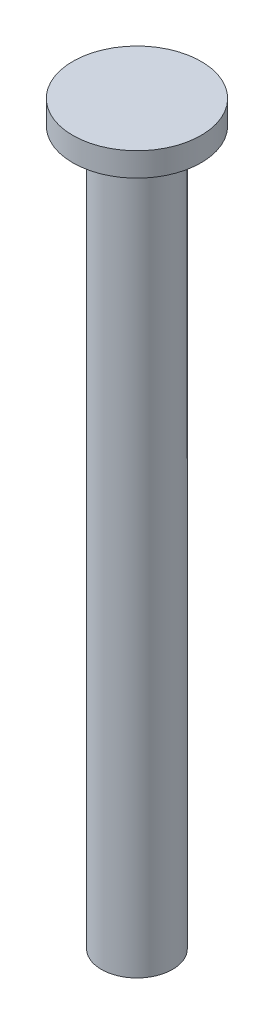
SolidWorks part; units mm, degrees
material "AISI 304"
ref_plane "Ön Düzlem" through (0, 0, 0) normal (0, 0, 1) x (1, 0, 0)
ref_plane "Üst Düzlem" through (0, 0, 0) normal (0, 1, 0) x (1, 0, 0)
ref_plane "Sağ Düzlem" through (0, 0, 0) normal (1, 0, 0) x (0, 0, -1)
sketch "Çizim2" plane through (0, 0, 0) normal (0, 1, 0) x (1, 0, 0)
  circle A0 centre (0, 0) radius 2.7
extrude "Yükseklik-Ekstrüzyon1" add sketch "Çizim2" along normal blind 1
sketch "Çizim3" plane through (0, 0, 0) normal (0, -1, 0) x (1, 0, 0)
  circle A0 centre (0, 0) radius 1.5
  dimension "D1" = 3
extrude "Yükseklik-Ekstrüzyon2" add sketch "Çizim3" along normal blind 30
